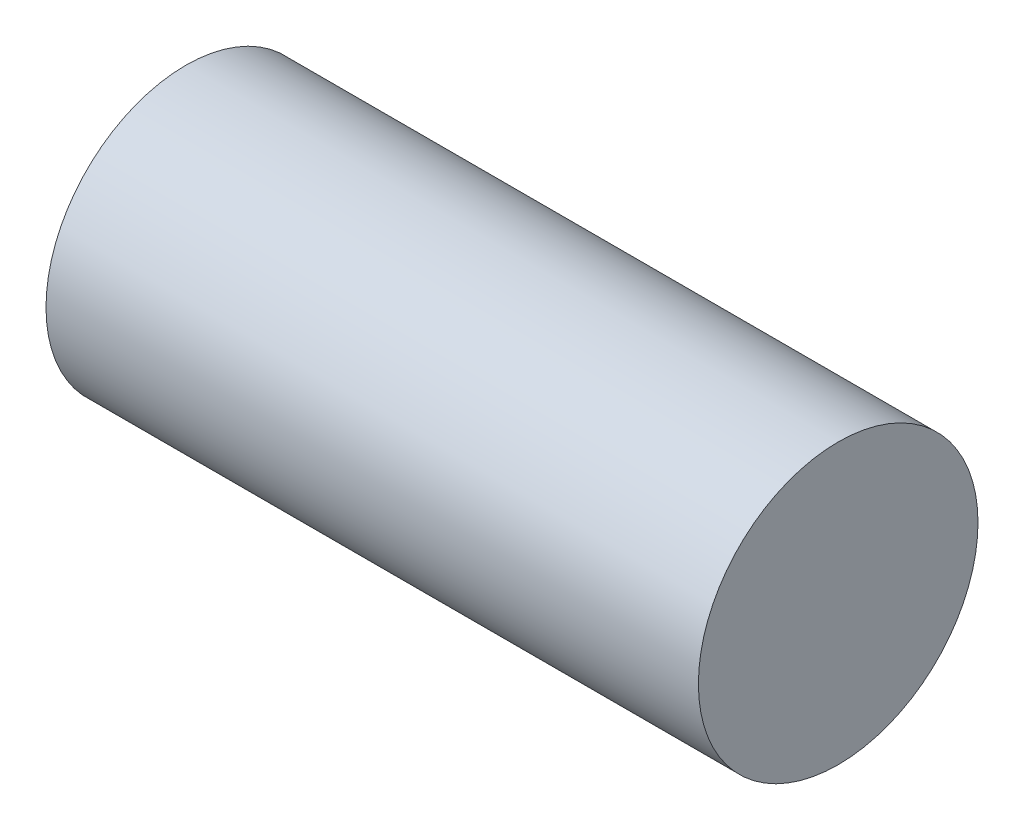
SolidWorks part; units mm, degrees
ref_plane "Front Plane" through (0, 0, 0) normal (0, 0, 1) x (1, 0, 0)
ref_plane "Top Plane" through (0, 0, 0) normal (0, 1, 0) x (1, 0, 0)
ref_plane "Right Plane" through (0, 0, 0) normal (1, 0, 0) x (0, 0, -1)
sketch "Sketch1" plane through (0, 0, 0) normal (1, 0, 0) x (0, 0, -1)
  circle A0 centre (0, 0) radius 15
  dimension "D1" = 30
extrude "Boss-Extrude1" add sketch "Sketch1" along normal blind 70
